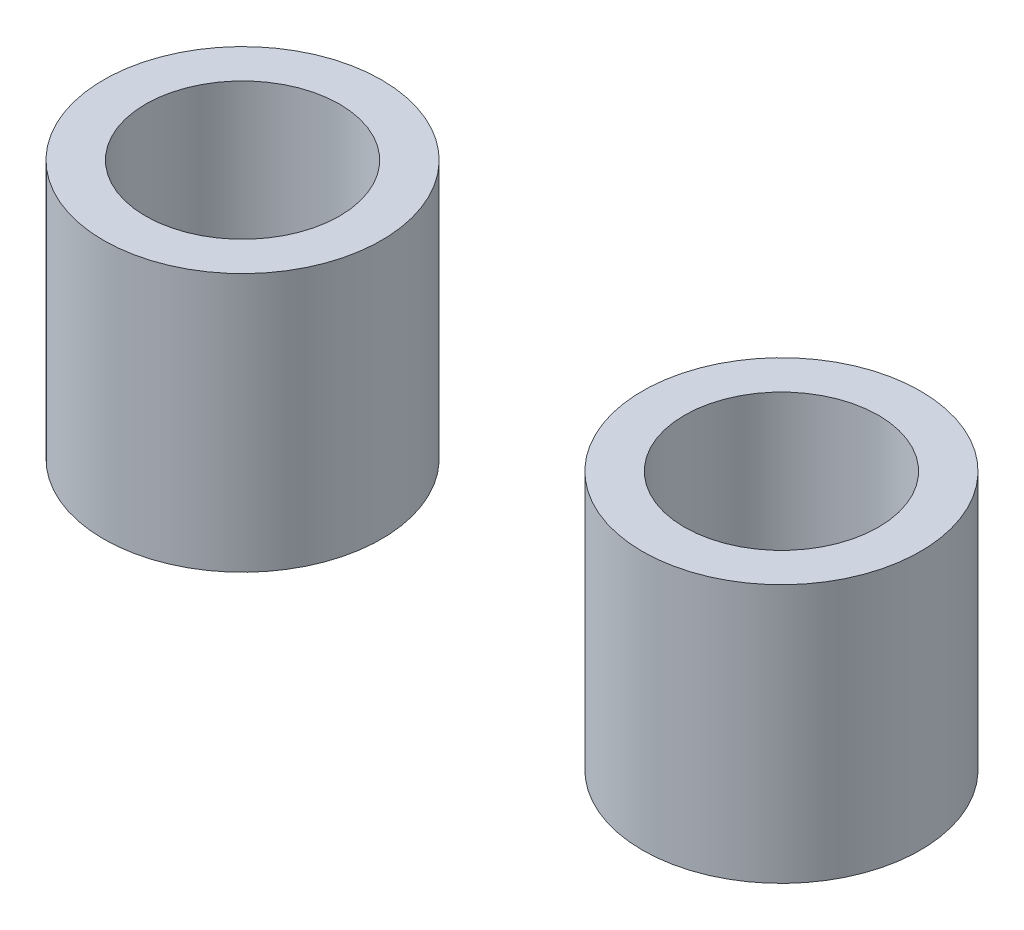
SolidWorks part; units mm, degrees
material "AISI 1020 Steel, Cold Rolled"
ref_plane "Front Plane" through (0, 0, 0) normal (0, 0, 1) x (1, 0, 0)
ref_plane "Top Plane" through (0, 0, 0) normal (0, 1, 0) x (1, 0, 0)
ref_plane "Right Plane" through (0, 0, 0) normal (1, 0, 0) x (0, 0, -1)
sketch "Sketch1" plane through (0, 0, 0) normal (0, 1, 0) x (1, 0, 0)
  circle A0 centre (0, 0) radius 1.143
  circle A1 centre (6.35, 0) radius 1.143
  circle A2 centre (6.35, 0) radius 1.6383
  circle A3 centre (0, 0) radius 1.6383
  dimension "D1" = 2.286
  dimension "D2" = 3.2766
  dimension "D3" = 6.35
extrude "Boss-Extrude1" add sketch "Sketch1" along normal blind 3.048
